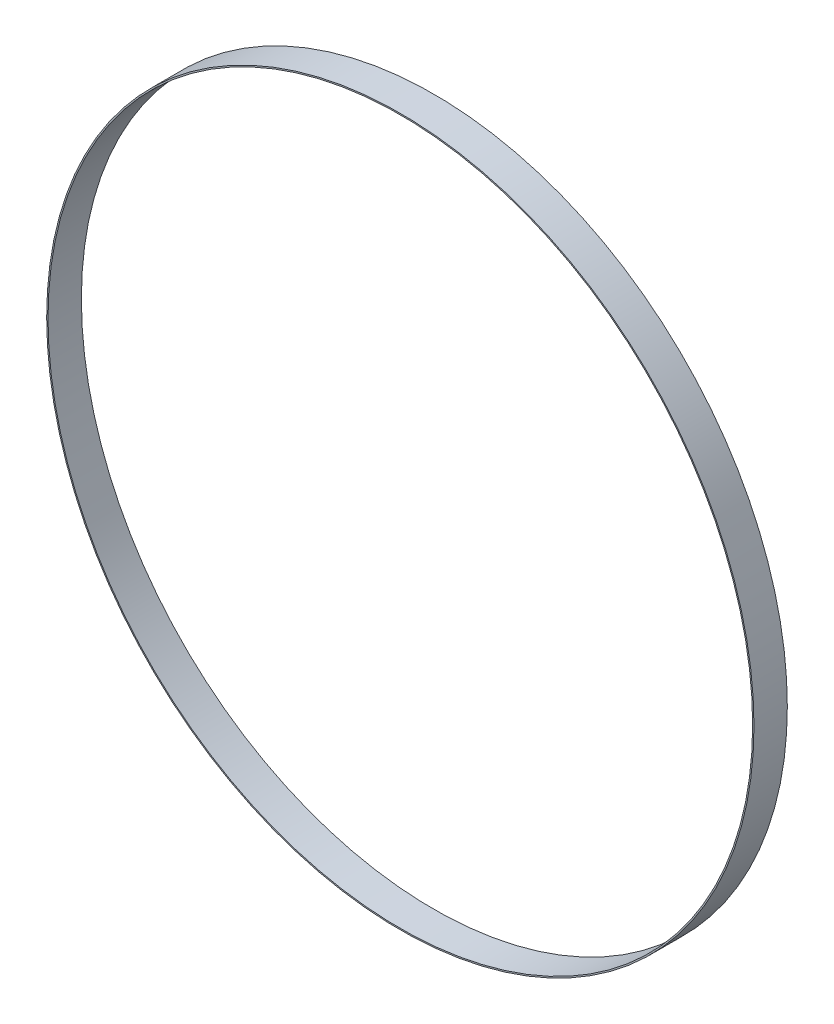
SolidWorks part; units mm, degrees
material "NBR"
ref_plane "Front Plane" through (0, 0, 0) normal (0, 0, 1) x (1, 0, 0)
ref_plane "Top Plane" through (0, 0, 0) normal (0, 1, 0) x (1, 0, 0)
ref_plane "Right Plane" through (0, 0, 0) normal (1, 0, 0) x (0, 0, -1)
sketch "Sketch1" plane through (0, 0, 0) normal (0, 0, 1) x (1, 0, 0)
  circle A0 centre (0, 0) radius 1056
  circle A1 centre (0, 0) radius 1060
  dimension "D1" = 2112
  dimension "D2" = 2120
extrude "Boss-Extrude1" add sketch "Sketch1" along normal blind 100
